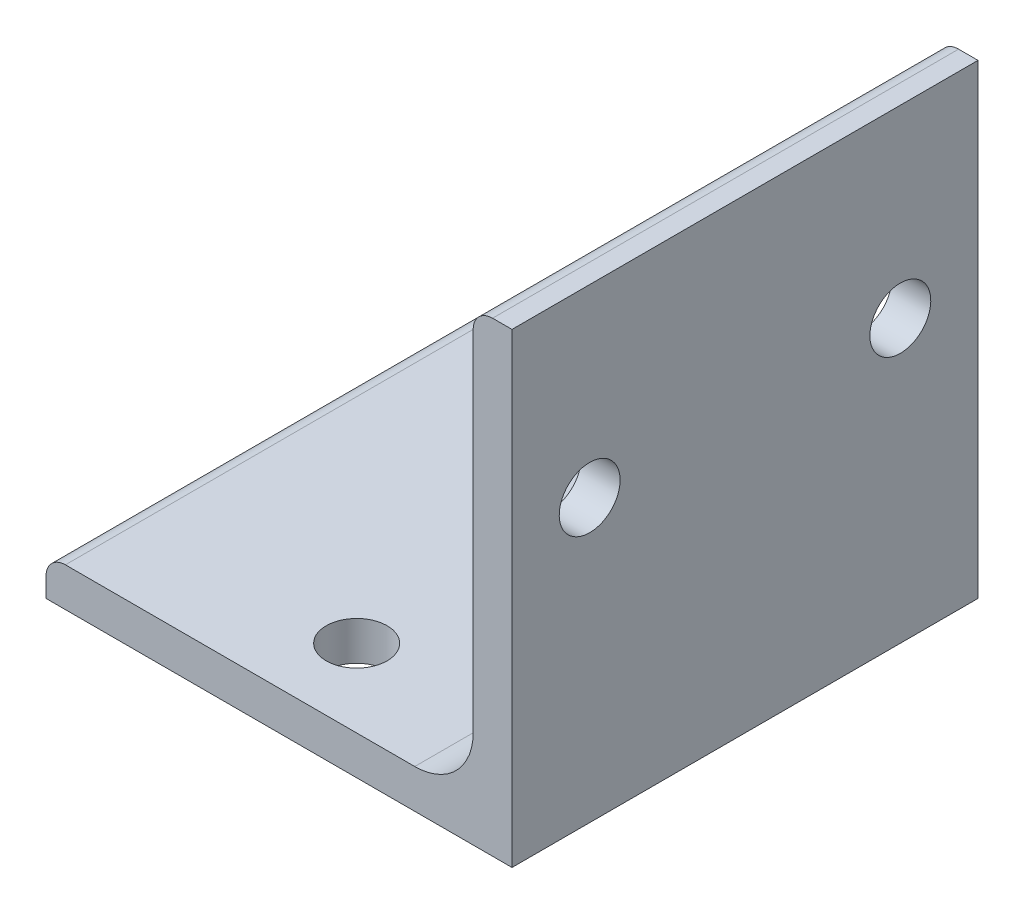
SolidWorks part; units mm, degrees
material "6061 Alloy"
ref_plane "Front Plane" through (0, 0, 0) normal (0, 0, 1) x (1, 0, 0)
ref_plane "Top Plane" through (0, 0, 0) normal (0, 1, 0) x (1, 0, 0)
ref_plane "Right Plane" through (0, 0, 0) normal (1, 0, 0) x (0, 0, -1)
sketch "Sketch0" plane through (0, 0, 0) normal (0, 0, 1) x (1, 0, 0)
  line L0 (-19.05, -19.05) -> (19.05, -19.05)
  line L1 (19.05, -19.05) -> (19.05, 19.05)
  line L2 (19.05, 0) -> (0, 0) construction
  line L3 (0, 0) -> (0, -19.05) construction
  line L4 (15.875, -11.0998) -> (15.875, 19.05) construction
  line L5 (11.0998, -15.875) -> (-19.05, -15.875) construction
  arc A0 (15.875, -11.0998) -> (11.0998, -15.875) centre (11.0998, -11.0998) cw
  point P3 (14.4764, -14.4764)
  dimension "Inside Corner Radius" = 4.7752
  dimension "Outside Height" = 38.1
  dimension "Inside Height" = 34.925
  dimension "Inside Width" = 34.925
  dimension "Wall Thickness" = 3.175
  dimension "D1" = 3.175
  dimension "Outside Width" = 38.1
sketch "Sketch1" plane through (0, 0, 0) normal (1, 0, 0) x (0, 0, -1)
  line L0 (19.05, 0) -> (-19.05, 0)
  point P4 (0, 0)
  dimension "Length" = 38.1
sketch "Sketch2" plane through (0, 0, 0) normal (0, 0, 1) x (1, 0, 0)
  line L0 (-19.05, -19.05) -> (19.05, -19.05)
  line L1 (19.05, -19.05) -> (19.05, 19.05)
  line L2 (19.05, 19.05) -> (15.875, 19.05) construction
  line L3 (15.875, 17.4625) -> (15.875, -11.0998)
  line L4 (11.0998, -15.875) -> (-17.4625, -15.875)
  line L5 (-19.05, -19.05) -> (-19.05, -15.875) construction
  line L6 (17.4625, 19.05) -> (19.05, 19.05)
  line L7 (-19.05, -17.4625) -> (-19.05, -19.05)
  line L8 (19.05, 0) -> (0, 0) construction
  line L9 (0, 0) -> (0, -19.05) construction
  arc A0 (15.875, 17.4625) -> (17.4625, 19.05) centre (17.4625, 17.4625) cw
  arc A1 (-19.05, -17.4625) -> (-17.4625, -15.875) centre (-17.4625, -17.4625) cw
  arc A2 (15.875, -11.0998) -> (11.0998, -15.875) centre (11.0998, -11.0998) cw
  dimension "Inside Radius" = 4.7752
  dimension "Height" = 38.1
  dimension "Width" = 38.1
  dimension "Thickness" = 3.175
extrude "Boss-Extrude1" add sketch "Sketch2" along normal mid plane 38.1
sketch "Break Locations" plane through (0, 0, 0) normal (1, 0, 0) x (0, 0, -1)
  line L0 (19.812, 0) -> (-19.812, 0)
  line L1 (-19.05, -19.05) -> (-19.05, 19.05) construction
  line L2 (19.05, -19.05) -> (19.05, 19.05) construction
  point P0 (13.335, 0)
  point P1 (-13.335, 0)
  point P10 (0, 0)
  point P11 (-19.812, 0)
  point P13 (19.812, 0)
  dimension "D1" = 32.385
  dimension "D2" = 32.385
  dimension "D3" = 38.862
sketch "Sketch3" plane through (19.05, 0, 0) normal (1, 0, 0) x (0, 0, -1)
  line L0 (0, -19.05) -> (0, 3.9687) construction
  line L1 (-19.05, -19.05) -> (19.05, -19.05) construction
  line L2 (0, 3.9687) -> (12.7, 3.9687) construction
  line L3 (0, 3.9687) -> (-12.7, 3.9687) construction
  circle A0 centre (-12.7, 3.9687) radius 2.4892
  circle A1 centre (12.7, 3.9687) radius 2.4892
  dimension "D1" = 23.0187
  dimension "D2" = 25.4
extrude "Cut-Extrude1" cut sketch "Sketch3" against normal through all
sketch "Sketch4" plane through (0, -19.05, 0) normal (0, -1, 0) x (1, 0, 0)
  line L0 (19.05, 0) -> (0, 0) construction
  line L1 (19.05, 19.05) -> (19.05, -19.05) construction
  line L2 (0, 0) -> (0, 12.7) construction
  line L3 (0, 0) -> (0, -12.7) construction
  circle A0 centre (0, 12.7) radius 2.4892
  circle A1 centre (0, -12.7) radius 2.4892
  dimension "D1" = 25.4
  dimension "D2" = 19.05
extrude "Cut-Extrude2" cut sketch "Sketch4" against normal through all
equation "\"D1@Break Locations\" = .85 * \"Height@Sketch2\""
equation "\"D2@Break Locations\"=\"D1@Break Locations\""
equation "\"Thickness@Sketch2\"=\"wall thickness@sketch0\""
equation "\"Height@Sketch2\"=\"outside height@sketch0\""
equation "\"Width@Sketch2\"=\"outside width@sketch0\""
equation "\"Inside Radius@Sketch2\"=\"inside corner radius@sketch0\""
equation "\"Length@Boss-Extrude1\"=\"length@sketch1\""
equation "\"D3@Break Locations\"=\"D2@Break Locations\"*1.2"
equation "\"D1@Sketch0\"=\"Wall Thickness@Sketch0\""
